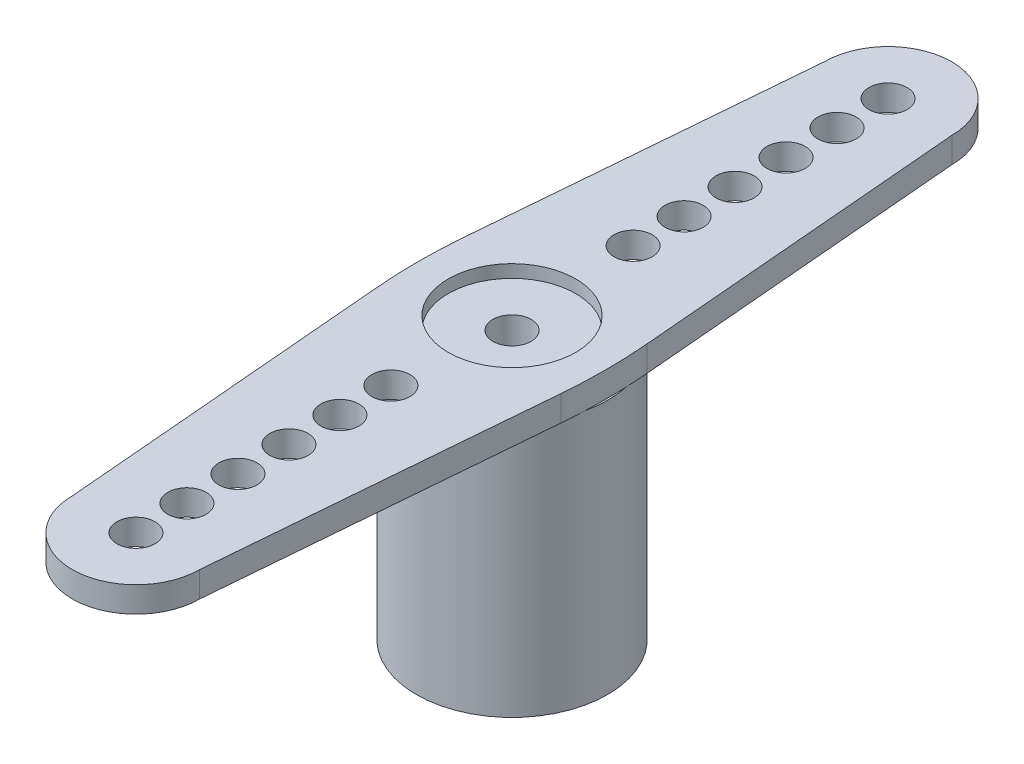
SolidWorks part; units mm, degrees
ref_plane "Front Plane" through (0, 0, 0) normal (0, 0, 1) x (1, 0, 0)
ref_plane "Top Plane" through (0, 0, 0) normal (0, 1, 0) x (1, 0, 0)
ref_plane "Right Plane" through (0, 0, 0) normal (1, 0, 0) x (0, 0, -1)
ref_plane "Plane1" through (0, 1, 0) normal (0, 1, 0) x (1, 0, 0)
sketch "Sketch1" plane through (0, 1, 0) normal (0, 1, 0) x (1, 0, 0)
  line L0 (-2.5, 14.75) -> (-3.6069, 1.6889)
  line L1 (-3.6069, -1.6889) -> (-2.5, -14.75)
  line L2 (2.5, -14.75) -> (3.6069, -1.6889)
  line L3 (3.6069, 1.6889) -> (2.5, 14.75)
  arc A0 (2.5, 14.75) -> (-2.5, 14.75) centre (0, 14.75) ccw
  arc A1 (-3.6069, 1.6889) -> (-3.6069, -1.6889) centre (16.3217, 0) ccw
  arc A2 (-2.5, -14.75) -> (2.5, -14.75) centre (0, -14.75) ccw
  arc A3 (3.6069, -1.6889) -> (3.6069, 1.6889) centre (-16.3217, 0) ccw
extrude "Boss-Extrude1" add sketch "Sketch1" against normal blind 1
sketch "Sketch2" plane through (0, 0, 0) normal (0, -1, 0) x (1, 0, 0)
  circle A0 centre (0, 0) radius 3.75
extrude "Boss-Extrude2" add sketch "Sketch2" along normal blind 10
sketch "Sketch3" plane through (0, -10, 0) normal (0, -1, 0) x (1, 0, 0)
  line L0 (0.1325, 2.3597) -> (0, 2.4922)
  line L1 (0, 2.4922) -> (-0.1325, 2.3597)
  line L2 (-0.1325, 2.3597) -> (-0.279, 2.4765)
  line L3 (-0.279, 2.4765) -> (-0.3959, 2.33)
  line L4 (-0.3959, 2.33) -> (-0.5546, 2.4297)
  line L5 (-0.5546, 2.4297) -> (-0.6543, 2.271)
  line L6 (-0.6543, 2.271) -> (-0.8231, 2.3523)
  line L7 (-0.8231, 2.3523) -> (-0.9044, 2.1835)
  line L8 (-0.9044, 2.1835) -> (-1.0813, 2.2454)
  line L9 (-1.0813, 2.2454) -> (-1.1432, 2.0685)
  line L10 (-1.1432, 2.0685) -> (-1.3259, 2.1102)
  line L11 (-1.3259, 2.1102) -> (-1.3676, 1.9275)
  line L12 (-1.3676, 1.9275) -> (-1.5748, 1.9508)
  line L13 (-1.5748, 1.9508) -> (-1.5748, 1.7622)
  line L14 (-1.5748, 1.7622) -> (-1.7622, 1.7622)
  line L15 (-1.7622, 1.7622) -> (-1.7622, 1.5748)
  line L16 (-1.7622, 1.5748) -> (-1.9508, 1.5748)
  line L17 (-1.9508, 1.5748) -> (-1.9275, 1.3676)
  line L18 (-1.9275, 1.3676) -> (-2.1102, 1.3259)
  line L19 (-2.1102, 1.3259) -> (-2.0685, 1.1432)
  line L20 (-2.0685, 1.1432) -> (-2.2454, 1.0813)
  line L21 (-2.2454, 1.0813) -> (-2.1835, 0.9044)
  line L22 (-2.1835, 0.9044) -> (-2.3523, 0.8231)
  line L23 (-2.3523, 0.8231) -> (-2.271, 0.6543)
  line L24 (-2.271, 0.6543) -> (-2.4297, 0.5546)
  line L25 (-2.4297, 0.5546) -> (-2.33, 0.3959)
  line L26 (-2.33, 0.3959) -> (-2.4765, 0.279)
  line L27 (-2.4765, 0.279) -> (-2.3597, 0.1325)
  line L28 (-2.3597, 0.1325) -> (-2.4922, 0)
  line L29 (-2.4922, 0) -> (-2.3597, -0.1325)
  line L30 (-2.3597, -0.1325) -> (-2.4765, -0.279)
  line L31 (-2.4765, -0.279) -> (-2.33, -0.3959)
  line L32 (-2.33, -0.3959) -> (-2.4297, -0.5546)
  line L33 (-2.4297, -0.5546) -> (-2.271, -0.6543)
  line L34 (-2.271, -0.6543) -> (-2.3523, -0.8231)
  line L35 (-2.3523, -0.8231) -> (-2.1835, -0.9044)
  line L36 (-2.1835, -0.9044) -> (-2.2454, -1.0813)
  line L37 (-2.2454, -1.0813) -> (-2.0685, -1.1432)
  line L38 (-2.0685, -1.1432) -> (-2.1102, -1.3259)
  line L39 (-2.1102, -1.3259) -> (-1.9275, -1.3676)
  line L40 (-1.9275, -1.3676) -> (-1.9508, -1.5748)
  line L41 (-1.9508, -1.5748) -> (-1.7622, -1.5748)
  line L42 (-1.7622, -1.5748) -> (-1.7622, -1.7622)
  line L43 (-1.7622, -1.7622) -> (-1.5748, -1.7622)
  line L44 (-1.5748, -1.7622) -> (-1.5748, -1.9508)
  line L45 (-1.5748, -1.9508) -> (-1.3676, -1.9275)
  line L46 (-1.3676, -1.9275) -> (-1.3259, -2.1102)
  line L47 (-1.3259, -2.1102) -> (-1.1432, -2.0685)
  line L48 (-1.1432, -2.0685) -> (-1.0813, -2.2454)
  line L49 (-1.0813, -2.2454) -> (-0.9044, -2.1835)
  line L50 (-0.9044, -2.1835) -> (-0.8231, -2.3523)
  line L51 (-0.8231, -2.3523) -> (-0.6543, -2.271)
  line L52 (-0.6543, -2.271) -> (-0.5546, -2.4297)
  line L53 (-0.5546, -2.4297) -> (-0.3959, -2.33)
  line L54 (-0.3959, -2.33) -> (-0.279, -2.4765)
  line L55 (-0.279, -2.4765) -> (-0.1325, -2.3597)
  line L56 (-0.1325, -2.3597) -> (0, -2.4922)
  line L57 (0, -2.4922) -> (0.1325, -2.3597)
  line L58 (0.1325, -2.3597) -> (0.279, -2.4765)
  line L59 (0.279, -2.4765) -> (0.3959, -2.33)
  line L60 (0.3959, -2.33) -> (0.5546, -2.4297)
  line L61 (0.5546, -2.4297) -> (0.6543, -2.271)
  line L62 (0.6543, -2.271) -> (0.8231, -2.3523)
  line L63 (0.8231, -2.3523) -> (0.9044, -2.1835)
  line L64 (0.9044, -2.1835) -> (1.0813, -2.2454)
  line L65 (1.0813, -2.2454) -> (1.1432, -2.0685)
  line L66 (1.1432, -2.0685) -> (1.3259, -2.1102)
  line L67 (1.3259, -2.1102) -> (1.3676, -1.9275)
  line L68 (1.3676, -1.9275) -> (1.5748, -1.9508)
  line L69 (1.5748, -1.9508) -> (1.5748, -1.7622)
  line L70 (1.5748, -1.7622) -> (1.7622, -1.7622)
  line L71 (1.7622, -1.7622) -> (1.7622, -1.5748)
  line L72 (1.7622, -1.5748) -> (1.9508, -1.5748)
  line L73 (1.9508, -1.5748) -> (1.9275, -1.3676)
  line L74 (1.9275, -1.3676) -> (2.1102, -1.3259)
  line L75 (2.1102, -1.3259) -> (2.0685, -1.1432)
  line L76 (2.0685, -1.1432) -> (2.2454, -1.0813)
  line L77 (2.2454, -1.0813) -> (2.1835, -0.9044)
  line L78 (2.1835, -0.9044) -> (2.3523, -0.8231)
  line L79 (2.3523, -0.8231) -> (2.271, -0.6543)
  line L80 (2.271, -0.6543) -> (2.4297, -0.5546)
  line L81 (2.4297, -0.5546) -> (2.33, -0.3959)
  line L82 (2.33, -0.3959) -> (2.4765, -0.279)
  line L83 (2.4765, -0.279) -> (2.3597, -0.1325)
  line L84 (2.3597, -0.1325) -> (2.4922, 0)
  line L85 (2.4922, 0) -> (2.3597, 0.1325)
  line L86 (2.3597, 0.1325) -> (2.4765, 0.279)
  line L87 (2.4765, 0.279) -> (2.33, 0.3959)
  line L88 (2.33, 0.3959) -> (2.4297, 0.5546)
  line L89 (2.4297, 0.5546) -> (2.271, 0.6543)
  line L90 (2.271, 0.6543) -> (2.3523, 0.8231)
  line L91 (2.3523, 0.8231) -> (2.1835, 0.9044)
  line L92 (2.1835, 0.9044) -> (2.2454, 1.0813)
  line L93 (2.2454, 1.0813) -> (2.0685, 1.1432)
  line L94 (2.0685, 1.1432) -> (2.1102, 1.3259)
  line L95 (2.1102, 1.3259) -> (1.9275, 1.3676)
  line L96 (1.9275, 1.3676) -> (1.9508, 1.5748)
  line L97 (1.9508, 1.5748) -> (1.7622, 1.5748)
  line L98 (1.7622, 1.5748) -> (1.7622, 1.7622)
  line L99 (1.7622, 1.7622) -> (1.5748, 1.7622)
  line L100 (1.5748, 1.7622) -> (1.5748, 1.9508)
  line L101 (1.5748, 1.9508) -> (1.3676, 1.9275)
  line L102 (1.3676, 1.9275) -> (1.3259, 2.1102)
  line L103 (1.3259, 2.1102) -> (1.1432, 2.0685)
  line L104 (1.1432, 2.0685) -> (1.0813, 2.2454)
  line L105 (1.0813, 2.2454) -> (0.9044, 2.1835)
  line L106 (0.9044, 2.1835) -> (0.8231, 2.3523)
  line L107 (0.8231, 2.3523) -> (0.6543, 2.271)
  line L108 (0.6543, 2.271) -> (0.5546, 2.4297)
  line L109 (0.5546, 2.4297) -> (0.3959, 2.33)
  line L110 (0.3959, 2.33) -> (0.279, 2.4765)
  line L111 (0.279, 2.4765) -> (0.1325, 2.3597)
extrude "Cut-Extrude1" cut sketch "Sketch3" against normal blind 3
draft "Draft1" type of draft neutral plane draft angle 6.429 faces to draft 1 face at (1.8565, -8.5, 1.5748) neutral plane through (1.7622, -7, 1.5748) neutral plane normal (-1, 0, 0) parameters "D1"=6.429
draft "Draft2" type of draft neutral plane draft angle 6.429 faces to draft 1 face at (1.5748, -8.5, 1.8565) neutral plane through (1.7622, -7, 1.7622) neutral plane normal (0, 0, -1) parameters "D1"=6.429
draft "Draft3" type of draft neutral plane draft angle 6.429 faces to draft 1 face at (1.5748, -8.5, -1.8565) neutral plane through (1.5748, -7, -1.7622) neutral plane normal (0, 0, 1) parameters "D1"=6.429
draft "Draft4" type of draft neutral plane draft angle 6.429 faces to draft 1 face at (1.8565, -8.5, -1.5748) neutral plane through (1.7622, -7, -1.7622) neutral plane normal (-1, 0, 0) parameters "D1"=6.429
draft "Draft5" type of draft neutral plane draft angle 6.429 faces to draft 1 face at (-1.8565, -8.5, -1.5748) neutral plane through (-1.7622, -7, -1.5748) neutral plane normal (1, 0, 0) parameters "D1"=6.429
draft "Draft6" type of draft neutral plane draft angle 6.429 faces to draft 1 face at (-1.5748, -8.5, -1.8565) neutral plane through (-1.7622, -7, -1.7622) neutral plane normal (0, 0, 1) parameters "D1"=6.429
draft "Draft7" type of draft neutral plane draft angle 6.429 faces to draft 1 face at (-1.5748, -8.5, 1.8565) neutral plane through (-1.5748, -7, 1.7622) neutral plane normal (0, 0, -1) parameters "D1"=6.429
draft "Draft8" type of draft neutral plane draft angle 6.429 faces to draft 1 face at (-1.8565, -8.5, 1.5748) neutral plane through (-1.7622, -7, 1.7622) neutral plane normal (1, 0, 0) parameters "D1"=6.429
hole_wizard "Ø1.5 (1.5) Diameter Hole1" positions "Sketch5" profile "Sketch4" hole size "Ø1.5" standard "ANSI Metric"
sketch "Sketch5" plane through (0, 0, 0) normal (0, -1, 0) x (-1, 0, 0)
  point P0 (0, 14.75)
  point P1 (0, 12.75)
  point P2 (0, 10.75)
  point P3 (0, 8.75)
  point P4 (0, 6.75)
  point P5 (0, 4.75)
  point P6 (0, -4.75)
  point P7 (0, -6.75)
  point P8 (0, -8.75)
  point P9 (0, -10.75)
  point P10 (0, -12.75)
  point P11 (0, -14.75)
sketch "Sketch4" plane through (0, 0, -14.75) normal (1, 0, 0) x (0, 0, -1)
  line L0 (0, 0) -> (0, 1)
  line L1 (0, 1) -> (0.75, 1)
  line L2 (0.75, 1) -> (0.75, 0)
  line L5 (0.75, 0) -> (0, 0)
  line L11 (0, -6.35) -> (0, 107.95) construction
  dimension "Thru Hole Dia." = 1.5
  dimension "Thru Hole Depth" = 1
hole_wizard "M5x0.8 Tapped Hole1" positions "Sketch7" profile "Sketch6" tap size "M5x0.8" standard "ANSI Metric"
sketch "Sketch7" plane through (0, 1, 0) normal (0, 1, 0) x (1, 0, 0)
  point P0 (0, 0)
sketch "Sketch6" plane through (0, 1, 0) normal (1, 0, 0) x (0, 0, 1)
  line L0 (0, 0) -> (0, 11)
  line L1 (0, 11) -> (0.75, 11)
  line L3 (0.75, 11) -> (0.75, 0.5)
  line L4 (0.75, 0.5) -> (2.5, 0.5)
  line L5 (2.5, 0.5) -> (2.5, 0)
  line L7 (2.5, 0) -> (0, 0)
  line L11 (0, -6.35) -> (0, 107.95) construction
  dimension "Thru Tap Drill Dia." = 1.5
  dimension "Thru Tap Drill Depth" = 11
  dimension "Thread Major Dia." = 5
  dimension "Thread Depth" = 0.5
